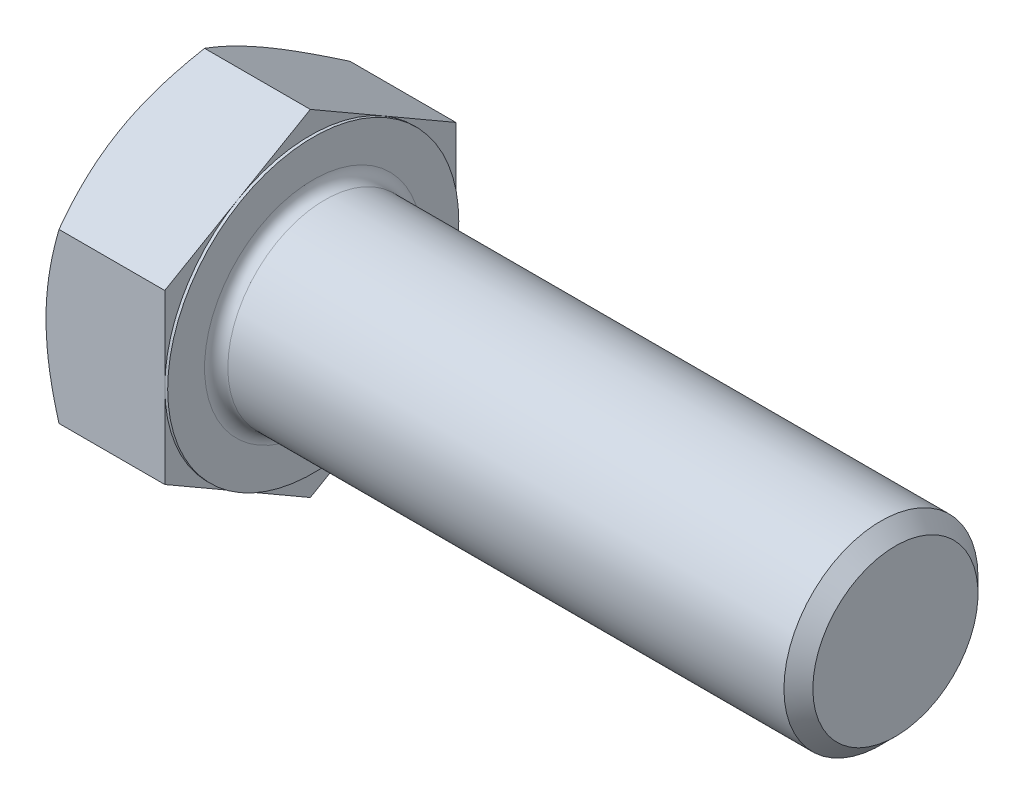
SolidWorks part; units mm, degrees
extrude "BaseHead" add sketch "Sketch1" along normal blind 15.9258
sketch "Sketch1" plane through (0, 0, 0) normal (1, 0, 0) x (0, 0, -1)
  line L0 (19.05, 10.9985) -> (19.05, -10.9985)
  line L1 (-19.05, 10.9985) -> (-19.05, -10.9985)
  line L2 (19.05, -10.9985) -> (0, -21.997)
  line L3 (0, -21.997) -> (-19.05, -10.9985)
  line L4 (19.05, 10.9985) -> (0, 21.997)
  line L5 (0, 21.997) -> (-19.05, 10.9985)
  dimension "Width_flats" = 38.1
  dimension "D2" = 120
  dimension "D3" = 19.05
  dimension "D4" = 19.05
  dimension "D5" = 19.05
revolve "HeadChamfer" cut sketch "Sketch3" angle 360 about L6
sketch "Sketch3" plane through (0, 0, 0) normal (0, 0, 1) x (1, 0, 0)
  line L0 (0, 19.05) -> (5.3677, 28.347)
  line L1 (0, 21.997) -> (0, 10.9985) construction
  line L2 (5.3677, 28.347) -> (5.3677, 34.697)
  line L3 (5.3677, 34.697) -> (-12.7, 34.697)
  line L4 (-12.7, 34.697) -> (-12.7, 19.05)
  line L5 (-12.7, 19.05) -> (0, 19.05)
  line L6 (0, 0) -> (99.06, 0) construction
  line L7 (15.9258, 21.997) -> (0, 21.997) construction
  dimension "D1" = 19.05
  dimension "D2" = 6.35
  dimension "D3" = 12.7
  dimension "D4" = 6.35
  dimension "Head_ch_ang" = 30
ref_plane "Plane1" through (0, 0, 0) normal (0, 0, 1) x (1, 0, 0)
ref_plane "Plane2" through (0, 0, 0) normal (0, 1, 0) x (1, 0, 0)
ref_plane "Plane3" through (0, 0, 0) normal (1, 0, 0) x (0, 0, -1)
sketch "BodySke" plane through (0, 0, 0) normal (0, 0, 1) x (1, 0, 0)
  line L0 (0, 10.9985) -> (0, -10.9985) construction
  line L1 (0, 0) -> (92.1258, 0)
  line L2 (0, 0) -> (0, 12.7)
  line L3 (0, 12.7) -> (90.2335, 12.7)
  line L4 (92.1258, 0) -> (92.1258, 10.8077)
  line L5 (15.9258, 21.997) -> (15.9258, 10.9985) construction
  line L6 (92.1258, 10.8077) -> (90.2335, 12.7)
  line L7 (0, 0) -> (96.52, 0) construction
  line L8 (92.1258, -10.8077) -> (90.2335, -12.7) construction
  line L9 (0, -12.7) -> (90.2335, -12.7) construction
  line L10 (18.034, 15.24) -> (18.034, -1.27) construction
  line L11 (60.3758, 15.24) -> (60.3758, -1.27) construction
  line L12 (15.9258, 10.9985) -> (15.9258, -10.9985) construction
  dimension "Diameter" = 25.4
revolve "BaseBody" add sketch "BodySke" angle 360 about L7
cosmetic thread "ThreadCosmetic" [suppressed] parameters "Thread_length"=31.75, "Thread_minor"=21.6154
sketch "Sketch4" plane through (0, 0, 0) normal (0, 0, 1) x (1, 0, 0)
  line L1 (15.9258, 21.997) -> (15.9258, 10.9985) construction
  line L2 (15.9258, 19.05) -> (15.5448, 19.05)
  line L3 (15.9258, 19.05) -> (15.9258, 47.397)
  line L4 (15.9258, 47.397) -> (15.5448, 47.397)
  line L5 (0, 0) -> (95.25, 0) construction
  line L6 (0, 0) -> (96.52, 0) construction
  line L7 (15.5448, 19.05) -> (15.5448, 47.397)
  line L8 (15.9258, 21.997) -> (1.7015, 21.997) construction
  dimension "D1" = 19.05
  dimension "D2" = 25.4
revolve "BearingFace" cut sketch "Sketch4" angle 360 about L5
fillet "HeadFillet" radius 1.524 1 edges at (15.9258, 0, -12.7)
sketch "ThdSchSke" plane through (0, 0, 0) normal (0, 0, 1) x (1, 0, 0)
  line L0 (60.3758, -10.8077) -> (59.0508, -12.7)
  line L1 (60.3758, -10.8077) -> (61.7008, -12.7)
  line L2 (61.7008, -12.7) -> (61.7008, -15.875)
  line L3 (-3.175, 0) -> (5.1513, 0) construction
  line L5 (61.7008, -15.875) -> (59.0508, -15.875)
  line L6 (59.0508, -15.875) -> (59.0508, -12.7)
  dimension "Thread_minor" = 21.6154
  dimension "Diameter" = 25.4
  dimension "Start" = 60.3758
revolve "ThreadSchematic" [suppressed] cut sketch "ThdSchSke" angle 360 about L3
pattern_linear "ThdSchPat" [suppressed]
equation "\"D3@Sketch1\" = \"Width_flats@Sketch1\" / 2"
equation "\"D4@Sketch1\" = \"D3@Sketch1\""
equation "\"D5@Sketch1\" = \"D4@Sketch1\""
equation "\"Thread_minor@ThreadCosmetic\" = \"Minor_dia@BodySke\""
equation "\"D1@Sketch3\" = \"Width_flats@Sketch1\" / 2"
equation "\"D1@Sketch4\" = \"Width_flats@Sketch1\" / 2"
equation "\"Thread_length@ThreadCosmetic\" = ((sgn( (\"Length@BodySke\" - \"Advance@BodySke\" ) - \"Thread_nom@BodySke\" )-1)*( (\"Length@BodySke\" - \"Advance@BodySke\" ) - \"Thread_nom@BodySke\" ))/-2+ \"Thread_nom@BodySke\""
equation "\"Thread_minor@ThdSchSke\" = \"Minor_dia@BodySke\""
equation "\"Diameter@ThdSchSke\" = \"Diameter@BodySke\""
equation "\"Overcut@ThdSchSke\" = \"Diameter@BodySke\" * 1.25"
equation "\"Start@ThdSchSke\" = \"Head_ht@BaseHead\" + \"Length@BodySke\" - \"Thread_length@ThreadCosmetic\"  '---Non-countersunk---"
equation "\"Num_threads@ThdSchPat\" = int( \"Thread_length@ThreadCosmetic\" / \"Advance@BodySke\" + 0.999 )  + 1"
equation "\"Advance@ThdSchPat\" = \"Thread_length@ThreadCosmetic\" /  (\"Num_threads@ThdSchPat\" - 1) 'relax it"
equation "\"Num_threads@ThdSchPat\" = \"Num_threads@ThdSchPat\" - sgn( \"Num_threads@ThdSchPat\" - 1) '---chamfered tips only---"
